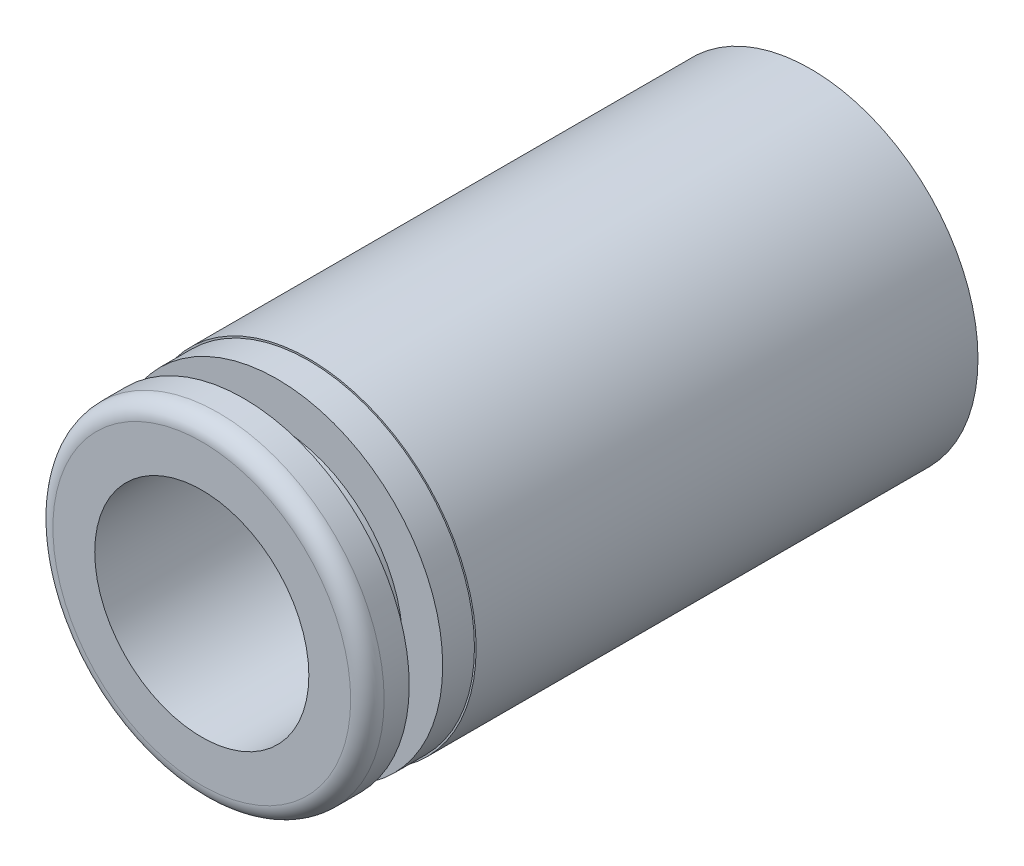
SolidWorks part; units mm, degrees
material "Plain Carbon Steel"
ref_plane "Front" through (0, 0, 0) normal (0, 0, 1) x (1, 0, 0)
ref_plane "Top" through (0, 0, 0) normal (0, 1, 0) x (1, 0, 0)
ref_plane "Right" through (0, 0, 0) normal (1, 0, 0) x (0, 0, -1)
sketch "Insert Sketch" plane through (0, 0, 0) normal (0, 0, 1) x (1, 0, 0)
  circle A0 centre (0, 0) radius 5
  circle A1 centre (0, 0) radius 3.2
  dimension "insert dia" = 10
  dimension "tube dia" = 6.4
extrude "Insert" add sketch "Insert Sketch" along normal blind 15
sketch "Sketch2" plane through (0, 0, 15) normal (0, 0, 1) x (1, 0, 0)
  circle A0 centre (0, 0) radius 4.95
  circle A1 centre (0, 0) radius 3.2 construction
  circle A2 centre (0, 0) radius 3.2
  dimension "chuck shoulder dia" = 9.9
extrude "chuck shoulder" add sketch "Sketch2" along normal blind 0.95
sketch "Sketch4" plane through (0, 0, 15.95) normal (0, 0, 1) x (1, 0, 0)
  circle A0 centre (0, 0) radius 3.75
  circle A1 centre (0, 0) radius 3.2 construction
  circle A2 centre (0, 0) radius 3.2
  dimension "chuck minor dia" = 7.5
extrude "chuck minor dia" add sketch "Sketch4" along normal blind 1
sketch "Sketch5" plane through (0, 0, 16.95) normal (0, 0, 1) x (1, 0, 0)
  circle A0 centre (0, 0) radius 3.2 construction
  circle A1 centre (0, 0) radius 3.2
  circle A2 centre (0, 0) radius 4.95 construction
  circle A3 centre (0, 0) radius 4.95
extrude "chuck top" add sketch "Sketch5" along normal blind 1.25
fillet "chuck top fillet" radius 0.5 1 edges at (4.95, 0, 18.2)
sketch "Sketch6" plane through (0, 0, 0) normal (0, 0, -1) x (-1, 0, 0)
  circle A0 centre (0, 0) radius 5
  circle A1 centre (0, 0) radius 10.8242
  dimension "D1" = 10
  dimension "D2" = 21.6485
extrude "Cut-Extrude1" [suppressed] cut sketch "Sketch6" against normal blind 13.5
sketch "Sketch7" [suppressed] plane through (0, 0, 15.1) normal (0, 0, 1) x (1, 0, 0)
  circle A0 centre (0, 0) radius 3 construction
  circle A1 centre (0, 0) radius 3
  circle A2 centre (0, 0) radius 4.7
  dimension "D1" = 7.5
extrude "elbow1" [suppressed] add sketch "Sketch7" along normal blind 2.14
ref_plane "Plane4" through (0, 0, 8.14) normal (0, 0, 1) x (1, 0, 0)
sketch "Sketch11" plane through (0, 0, 8.14) normal (0, 0, 1) x (1, 0, 0)
  line L0 (5.2, 0) -> (5.2, 15)
  line L1 (-5.2, 0) -> (-5.2, 15)
  line L2 (5.2, 15) -> (-5.2, 15)
  line L3 (-5.2, 0) -> (5.2, 0)
  dimension "D1" = 15
  dimension "D2" = 10.4
extrude "elbow box" [suppressed] add sketch "Sketch11" along normal blind 24
sketch "Sketch12" [suppressed] plane through (0, 0, 29.5) normal (0, 0, 1) x (1, 0, 0)
  line L1 (0, 0) -> (-4.7, 0)
  line L2 (0, 0) -> (0, -6.2365) construction
  line L3 (0, 0) -> (0, -4.7)
  arc A0 (-4.7, 0) -> (4.7, 0) centre (0, 0) ccw construction
  arc A1 (-4.7, 0) -> (0, -4.7) centre (0, 0) ccw
revolve "Boss-Revolve1" [suppressed] add sketch "Sketch12" angle 360 about L2
ref_plane "Plane5" through (0, 0, 25.14) normal (0, 0, 1) x (1, 0, 0)
sketch "Sketch14" [suppressed] plane through (0, 0, 48) normal (0, 0, 1) x (1, 0, 0)
  line L1 (-4.7, 0) -> (4.7, 0) construction
  line L2 (0, -24.0553) -> (0, 4.3854) construction
  line L3 (-4.7, 0) -> (-4.7, -15)
  line L4 (-4.7, 0) -> (0, 0)
  line L5 (0, 0) -> (0, -15)
  line L6 (-4.7, -15) -> (0, -15)
  dimension "D1" = 11
revolve "elbow3" [suppressed] add sketch "Sketch14" angle 360 about L2
sketch "Sketch15" [suppressed] plane through (0, 0, 48) normal (0, 0, 1) x (1, 0, 0)
  line L2 (-4.7, -15) -> (4.7, -15) construction
  line L3 (-4.7, -15) -> (4.7, -15) construction
  circle A0 centre (0, -15) radius 4.7
extrude "elbow4" [suppressed] add sketch "Sketch15" against normal up to surface (32.9 mm away)
sketch "Sketch16" [suppressed] plane through (0, 0, 48) normal (0, 0, 1) x (1, 0, 0)
  line L0 (-4.7, -15) -> (4.7, -15) construction
  line L2 (0, -15) -> (0, -29.5248) construction
  line L3 (-4.7, -15) -> (0, -15)
  line L4 (0, -15) -> (0, -19.7)
  arc A1 (-4.7, -15) -> (4.7, -15) centre (0, -15) ccw construction
  arc A2 (-4.7, -15) -> (0, -19.7) centre (0, -15) ccw
revolve "elbow6" [suppressed] add sketch "Sketch16" angle 360 about L2
sketch "Sketch18" [suppressed] plane through (0, 18.5, 0) normal (0, 1, 0) x (-1, 0, 0)
  circle A0 centre (0, 48) radius 6.75
  circle A1 centre (0, 48) radius 4.7 construction
  circle A2 centre (0, 48) radius 4
  dimension "hor. chuck shoulder" = 10
  dimension "hor. chuck fitting dia." = 7.9
extrude "hor. chuck shoulder" [suppressed] add sketch "Sketch18" along normal blind 0.75
sketch "Sketch19" [suppressed] plane through (0, 19.25, 0) normal (0, 1, 0) x (-1, 0, 0)
  line L1 (0, 15.1) -> (0, 48) construction
  circle A0 centre (0, 48) radius 4.5
  circle A1 centre (0, 48) radius 4 construction
  circle A2 centre (0, 48) radius 4
  dimension "hor. chuck minor dia." = 6.5
extrude "hor. chuck minor dia" [suppressed] add sketch "Sketch19" along normal blind 1
sketch "Sketch20" [suppressed] plane through (0, 20.25, 0) normal (0, 1, 0) x (-1, 0, 0)
  line L0 (0, 15.1) -> (0, 48) construction
  circle A0 centre (0, 48) radius 6.75
  circle A1 centre (0, 48) radius 4 construction
  circle A2 centre (0, 48) radius 4
  circle A4 centre (0, 48) radius 6.75 construction
extrude "hor. chuck top" [suppressed] add sketch "Sketch20" along normal blind 1.25
fillet "Fillet1" [suppressed] radius 0.5
pattern_linear "hor. chuck pattern" [suppressed] count 11 spacing 11
pattern_linear "LPattern1" [suppressed] count 2 spacing 11
sketch "Sketch23" [suppressed] plane through (0, 0, 0) normal (0, -1, 0) x (1, 0, 0)
  circle A0 centre (0, 48) radius 4.7 construction
  circle A3 centre (0, 48) radius 4
  dimension "D1" = 4.5
extrude "hor. chuck insert" [suppressed] cut sketch "Sketch23" against normal through all
sketch "Sketch26" [suppressed] plane through (0, 0, 0) normal (0, -1, 0) x (1, 0, 0)
  circle A0 centre (0, 29.5) radius 4
  arc A1 (4.7, 29.5) -> (-4.7, 29.5) centre (0, 29.5) ccw construction
  dimension "D1" = 6.8105
extrude "hor. chuck insert 2" [suppressed] cut sketch "Sketch26" against normal through all
sketch "Sketch27" plane through (0, 0, 0) normal (0, 0, 1) x (1, 0, 0)
  circle A0 centre (0, 0) radius 0.5
  dimension "D1" = 1
extrude "solid plug" [suppressed] add sketch "Sketch27" along normal blind 16.8
chamfer "Chamfer1" [suppressed] distance 0.5 angle 45
sketch "M5 Boss Sketch" [suppressed] plane through (0, 0, 13) normal (0, 0, 1) x (1, 0, 0)
  line L0 (5, 5) -> (-5, -5) construction
  line L1 (-5, -5) -> (5, -5)
  line L2 (-5, -5) -> (-5, 5)
  line L3 (-5, 5) -> (5, 5)
  line L4 (5, -5) -> (5, 5)
  circle A0 centre (0, 0) radius 2.5 construction
  circle A1 centre (0, 0) radius 2.5
  dimension "D1" = 10
extrude "M5 Boss" [suppressed] add sketch "M5 Boss Sketch" along normal blind 1.5
